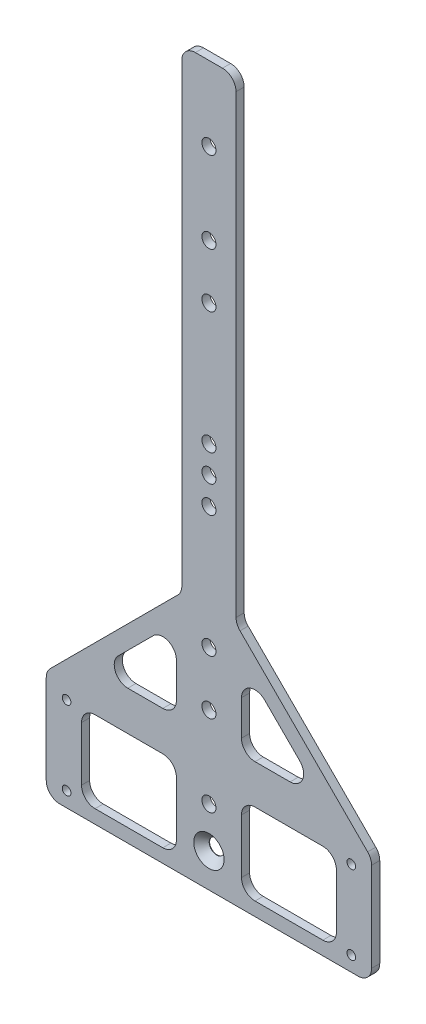
SolidWorks part; units mm, degrees
material "Thornel Mat VMA"
ref_plane "前视基准面" through (0, 0, 0) normal (0, 0, 1) x (1, 0, 0)
ref_plane "上视基准面" through (0, 0, 0) normal (0, 1, 0) x (1, 0, 0)
ref_plane "右视基准面" through (0, 0, 0) normal (1, 0, 0) x (0, 0, -1)
sketch "草图1" plane through (0, 0, 0) normal (0, 0, 1) x (1, 0, 0)
  line L0 (-52.5, 0) -> (52.5, 0) construction
  line L1 (-60, 20) -> (60, 20) construction
  line L2 (-60, 20) -> (-60, -20)
  line L3 (-60, -20) -> (60, -20)
  line L4 (60, 20) -> (60, -20)
  line L5 (-60, 20) -> (60, -20) construction
  line L6 (-60, -20) -> (60, 20) construction
  line L7 (-52.5, 14.5) -> (-52.5, -14.5) construction
  line L8 (52.5, 14.5) -> (52.5, -14.5) construction
  line L9 (0, 7.5) -> (0, -7.5) construction
  line L10 (-60, 20) -> (-10, 70)
  line L11 (-10, 70) -> (-10, 245)
  line L12 (-10, 245) -> (10, 245)
  line L13 (10, 245) -> (10, 70)
  line L14 (10, 70) -> (60, 20)
  line L15 (0, 245) -> (0, 20) construction
  circle A0 centre (-52.5, -14.5) radius 1.6
  circle A1 centre (52.5, -14.5) radius 1.6
  circle A2 centre (52.5, 14.5) radius 1.6
  circle A3 centre (-52.5, 14.5) radius 1.6
  circle A4 centre (0, 7.5) radius 2.6
  circle A5 centre (0, -7.5) radius 2.6
  point P0 (0, 0)
  point P27 (0, 0)
  dimension "D3" = 3.2
  dimension "D7" = 5.2
  dimension "D1" = 105
  dimension "D2" = 120
  dimension "D4" = 40
  dimension "D5" = 29
  dimension "D6" = 15
  dimension "D8" = 20
  dimension "D9" = 45
  dimension "D10" = 225
extrude "凸台-拉伸1" add sketch "草图1" along normal mid plane 3
sketch "草图2" plane through (0, 0, 1.5) normal (0, 0, 1) x (1, 0, 0)
  circle A1 centre (0, 217.5) radius 2.6
  circle A2 centre (0, 187.5) radius 2.6
  circle A3 centre (0, 167.5) radius 2.6
  circle A5 centre (0, 122.5) radius 2.6
  circle A6 centre (0, 112.5) radius 2.6
  circle A7 centre (0, 102.5) radius 2.6
  circle A8 centre (0, 57.5) radius 2.6
  circle A9 centre (0, 37.5) radius 2.6
  point P0 (0, 37.5)
  point P1 (0, 57.5)
  point P3 (0, 122.5)
  point P5 (0, 112.5)
  point P7 (0, 102.5)
  point P9 (0, 167.5)
  point P11 (0, 187.5)
  point P13 (0, 217.5)
  dimension "D1" = 5.2
extrude "切除-拉伸1" cut sketch "草图2" against normal through all
sketch "草图3" plane through (0, 0, 1.5) normal (0, 0, 1) x (1, 0, 0)
  line L0 (0, -20) -> (0, 75.0546) construction
  line L1 (-60, -20) -> (60, -20) construction
  line L2 (-12, -20) -> (-12, 75.0546)
  line L3 (-12, 59.5147) -> (-42, 29.5147)
  line L4 (-42, 29.5147) -> (-12, 29.5147)
  line L5 (-10, 70) -> (-60, 20) construction
  line L7 (-12, 15) -> (-47, 15)
  line L8 (-12, 15) -> (-12, -15)
  line L9 (-12, -15) -> (-47, -15)
  line L10 (-47, 15) -> (-47, -15)
  dimension "D2" = 6
  dimension "D3" = 30
  dimension "D4" = 30
  dimension "D5" = 5
  dimension "D6" = 35
  dimension "D1" = 12
extrude "切除-拉伸2" cut sketch "草图3" against normal through all contours L3 L4 L2 | L7 L10 L9 L2
mirror "镜向1" about plane through (0, 0, 0) normal (1, 0, 0) of "切除-拉伸2"
fillet "圆角1" radius 5 22 edges at (12, 29.5147, 0) (42, 29.5147, 0) (12, 59.5147, 0) (12, -15, 0) (47, -15, 0) (47, 15, 0) (12, 15, 0) (60, -20, 0) (-60, 20, 0) (-10, 70, 0) (-10, 245, 0) (10, 245, 0) (10, 70, 0) (60, 20, 0) (-47, 15, 0) (-47, -15, 0) (-12, -15, 0) (-12, 15, 0) (-42, 29.5147, 0) (-12, 29.5147, 0) (-12, 59.5147, 0) (-60, -20, 0)
hole_wizard "M5 六角凹锥坑螺钉的锥形沉头孔1" positions "草图4" profile "草图5" countersink size "M5" standard "ISO" end condition through all
sketch "草图4" plane through (0, 0, 1.5) normal (0, 0, 1) x (1, 0, 0)
  point P0 (0, -7.5)
sketch "草图5" plane through (0, -7.5, 1.5) normal (1, 0, 0) x (0, -1, 0)
  line L0 (0, 0) -> (0, 3)
  line L1 (0, 3) -> (2.75, 3)
  line L2 (2.75, 3) -> (2.75, 2.85)
  line L3 (2.75, 2.85) -> (5.6, 0)
  line L5 (5.6, 0) -> (0, 0)
  line L6 (-2.75, 2.85) -> (-5.6, 0) construction
  line L11 (0, -6.35) -> (0, 107.95) construction
  dimension "通孔孔直径" = 5.5
  dimension "通孔孔深度" = 3
  dimension "近端锥形沉头孔直径" = 11.2
  dimension "近端锥形沉头孔角度" = 90
